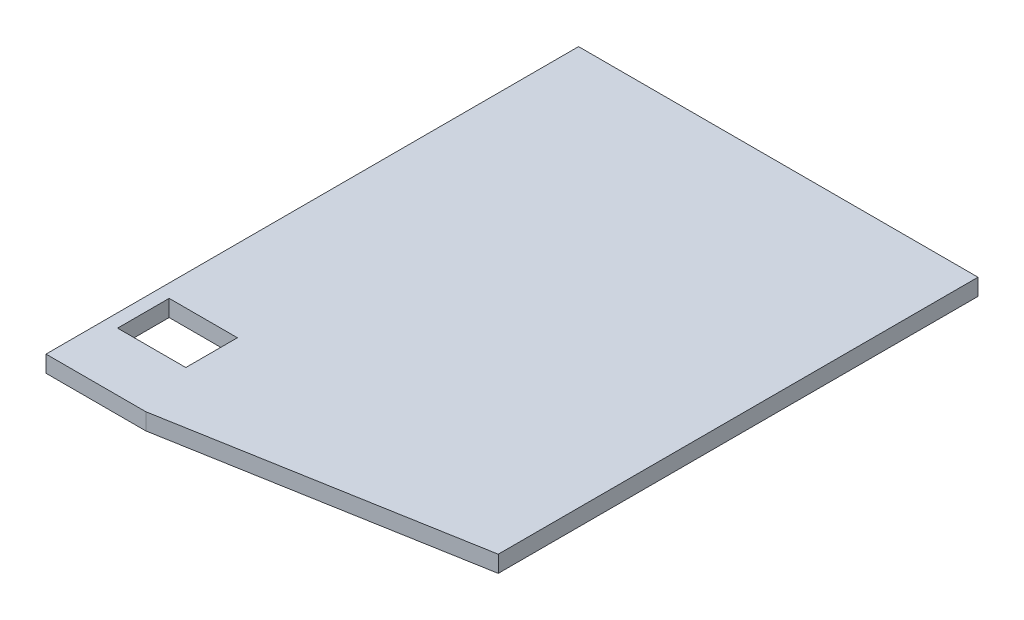
SolidWorks part; units mm, degrees
ref_plane "前视基准面" through (0, 0, 0) normal (1, 0, 0) x (0, 1, 0)
ref_plane "上视基准面" through (0, 0, 0) normal (0, 0, 1) x (0, 1, 0)
ref_plane "右视基准面" through (0, 0, 0) normal (0, 1, 0) x (-1, 0, 0)
other "Configuration Table"
sketch "草图3" plane through (0, 0, 0) normal (0, 0, 1) x (0, 1, 0)
  line L1 (0, 0) -> (2.5, 0)
  line L2 (0, 0) -> (0, -24)
  line L3 (0, -24) -> (2.5, -24)
  line L4 (2.5, 0) -> (2.5, -24)
  line L5 (0, 0) -> (2.5, -24) construction
  line L6 (0, -24) -> (2.5, 0) construction
  point P4 (1.25, -12)
  dimension "D1" = 2.5
  dimension "D2" = 24
extrude "凸台-拉伸1" add sketch "草图3" along normal blind 33
fillet "圆角1" radius 1 1 edges at (24, 2.5, 16.5)
sketch "草图4" plane through (0, 0, 0) normal (0, -1, 0) x (1, 0, 0)
  line L0 (3, 33) -> (3, 0) construction
  line L1 (0, 33) -> (24, 33) construction
  line L2 (0, 0) -> (24, 0) construction
  line L3 (0, 33) -> (0, 0) construction
  line L4 (3, 33) -> (24, 31.1627)
  line L5 (24, 33) -> (24, 0) construction
  line L6 (24, 31.1627) -> (24, 33)
  line L7 (24, 33) -> (3, 33)
  dimension "D1" = 3
  dimension "D2" = 5
extrude "切除-拉伸1" cut sketch "草图4" against normal through all
sketch "草图5" plane through (0, 0, 0) normal (-1, 0, 0) x (0, -1, 0)
  line L0 (-2.5, 33) -> (-2.5, 0) construction
  line L1 (-2.5, 28.5) -> (0, 28.5)
  line L2 (-2.5, 28.5) -> (-2.5, 25.4)
  line L3 (-2.5, 25.4) -> (0, 25.4)
  line L4 (0, 28.5) -> (0, 25.4)
  line L5 (-2.5, 28.5) -> (0, 25.4) construction
  line L6 (-2.5, 25.4) -> (0, 28.5) construction
  line L7 (0, 33) -> (0, 0) construction
  line L8 (-2.5, 33) -> (0, 33) construction
  point P4 (-1.25, 26.95)
  dimension "D1" = 4.5
  dimension "D2" = 3.1
extrude "切除-拉伸2" cut sketch "草图5" against normal blind 4.9
sketch "草图6" plane through (0, 0, 33) normal (0, 0, 1) x (1, 0, 0)
  line L1 (24, 0) -> (0, 0)
  line L2 (24, 0) -> (24, 2.5)
  line L3 (24, 2.5) -> (0, 2.5)
  line L4 (0, 0) -> (0, 2.5)
  line L5 (24, 0) -> (0, 2.5) construction
  line L6 (24, 2.5) -> (0, 0) construction
  point P4 (12, 1.25)
extrude "切除-拉伸3" cut sketch "草图6" against normal blind 1
sketch "草图7" plane through (0, 0, 0) normal (0, -1, 0) x (1, 0, 0)
  line L0 (24, 31.1627) -> (24, 0) construction
  line L1 (0, 32) -> (14.4301, 32) construction
  line L2 (14.4301, 32) -> (24, 31.1627) construction
  line L3 (24, 31.1627) -> (24, 28.8261)
  line L4 (6, 32) -> (14.4301, 32)
  line L5 (14.4301, 32) -> (24, 31.1627)
  line L6 (6, 32) -> (24, 28.8261)
  dimension "D1" = 6
  dimension "D2" = 10
extrude "切除-拉伸4" cut sketch "草图7" against normal through all
sketch "草图8" plane through (0, 2.5, 0) normal (0, 1, 0) x (-1, 0, 0)
  line L0 (-4.9, 25.4) -> (0, 25.4) construction
  line L1 (0, 28.5) -> (-0.8, 28.5)
  line L2 (0, 28.5) -> (0, 25.4)
  line L3 (0, 25.4) -> (-0.8, 25.4)
  line L4 (-0.8, 28.5) -> (-0.8, 25.4)
  line L5 (0, 28.5) -> (-0.8, 25.4) construction
  line L6 (0, 25.4) -> (-0.8, 28.5) construction
  line L7 (-4.9, 28.5) -> (-4.9, 25.4) construction
  point P4 (-0.4, 26.95)
  dimension "D1" = 4.1
  dimension "D2" = 0.8
extrude "凸台-拉伸2" add sketch "草图8" against normal up to surface (2.5 mm away) up to face at (7.0889, 0, 22.2918)
ref_plane "基准面1" through (0, 1, 0) normal (0, -1, 0) x (-1, 0, 0)
sketch "草图10" plane through (0, 1, 0) normal (0, -1, 0) x (-1, 0, 0)
  line L4 (-0.8, -28.5) -> (-0.8, -25.4)
  line L5 (-4.9, -28.5) -> (-0.8, -28.5)
  line L6 (-4.9, -25.4) -> (-4.9, -28.5)
  line L7 (-0.8, -25.4) -> (-4.9, -25.4)
  line L8 (-0.8, -28.5) -> (-0.8, -25.4)
  line L9 (-4.9, -28.5) -> (-0.8, -28.5)
  line L10 (-4.9, -25.4) -> (-4.9, -28.5)
  line L11 (-0.8, -25.4) -> (-4.9, -25.4)
  line L13 (-6, -32) -> (0, -32)
  line L14 (0, -32) -> (0, 0)
  line L15 (0, 0) -> (-24, 0)
  line L16 (-24, 0) -> (-24, -28.8261)
  line L17 (-24, -28.8261) -> (-6, -32)
  line L18 (-6, -32) -> (0, -32)
  line L19 (0, -32) -> (0, 0)
  line L20 (0, 0) -> (-24, 0)
  line L21 (-24, 0) -> (-24, -28.8261)
  line L22 (-24, -28.8261) -> (-6, -32)
  dimension "D1" = 0
  dimension "D2" = 0
extrude "切除-拉伸5" cut sketch "草图10" against normal through all
